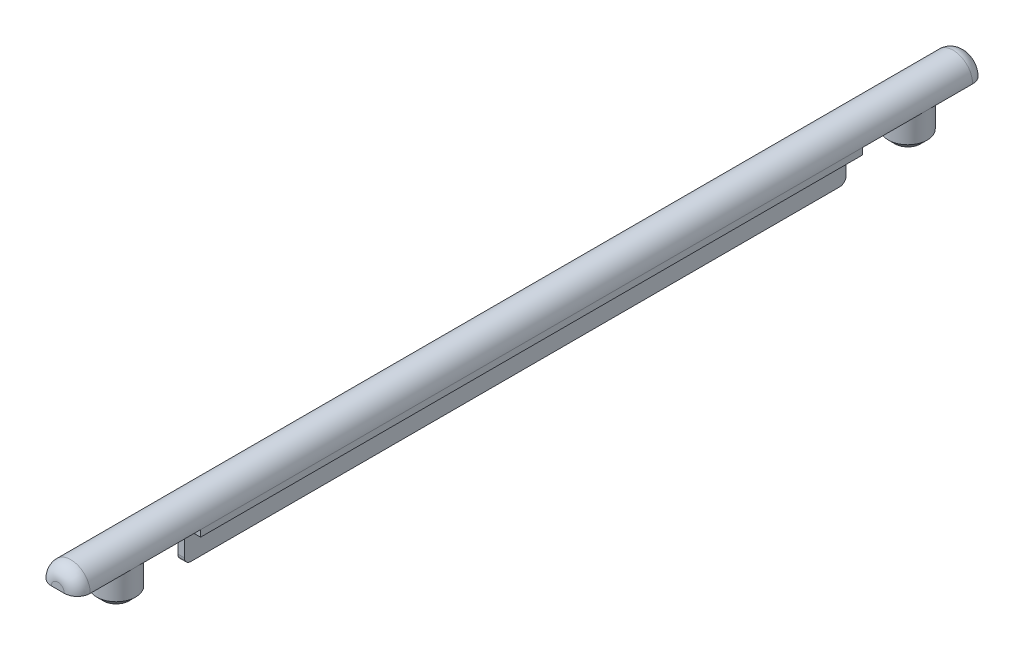
SolidWorks part; units mm, degrees
ref_plane "前视" through (0, 0, 0) normal (0, 0, 1) x (1, 0, 0)
ref_plane "上视" through (0, 0, 0) normal (0, 1, 0) x (1, 0, 0)
ref_plane "右视" through (0, 0, 0) normal (1, 0, 0) x (0, 0, -1)
sketch "草图2" plane through (0, 0, 0) normal (0, 0, 1) x (1, 0, 0)
  line L0 (-3, 0) -> (3, 0)
  line L1 (-3, 0) -> (-3, 1)
  line L2 (3, 0) -> (3, 1)
  arc A2 (3, 1) -> (-3, 1) centre (0, 1) ccw
extrude "凸台-拉伸2" add sketch "草图2" along normal blind 140
sketch "草图4" plane through (0, 0, 0) normal (0, -1, 0) x (1, 0, 0)
  line L1 (-3, 140) -> (3, 140)
  line L2 (-3, 140) -> (-3, 121)
  line L3 (-3, 121) -> (3, 121)
  line L4 (3, 140) -> (3, 121)
  line L5 (3, 0) -> (-3, 0)
  line L6 (3, 0) -> (3, 19)
  line L7 (3, 19) -> (-3, 19)
  line L8 (-3, 0) -> (-3, 19)
extrude "切除-拉伸1" cut sketch "草图4" against normal blind 1
sketch "草图3" plane through (0, 1, 0) normal (0, -1, 0) x (1, 0, 0)
  circle A2 centre (0, 131) radius 3
  circle A3 centre (0, 9) radius 3
extrude "凸台-拉伸4" add sketch "草图3" along normal blind 5
chamfer "倒角2" distance 1 angle 45 2 edges at (0, -4, 128) (0, -4, 6)
fillet "圆角2" radius 2 2 edges at (0, 4, 0) (0, 4, 140)
sketch "草图5" plane through (0, 0, 0) normal (0, -1, 0) x (1, 0, 0)
  line L0 (-0.5, 121) -> (0.5, 121)
  line L1 (-0.5, 121) -> (-0.5, 19)
  line L2 (-0.5, 19) -> (0.5, 19)
  line L3 (0.5, 121) -> (0.5, 19)
extrude "凸台-拉伸5" add sketch "草图5" along normal blind 5
fillet "圆角3" radius 1 2 edges at (0, -5, 19) (0, -5, 121)
